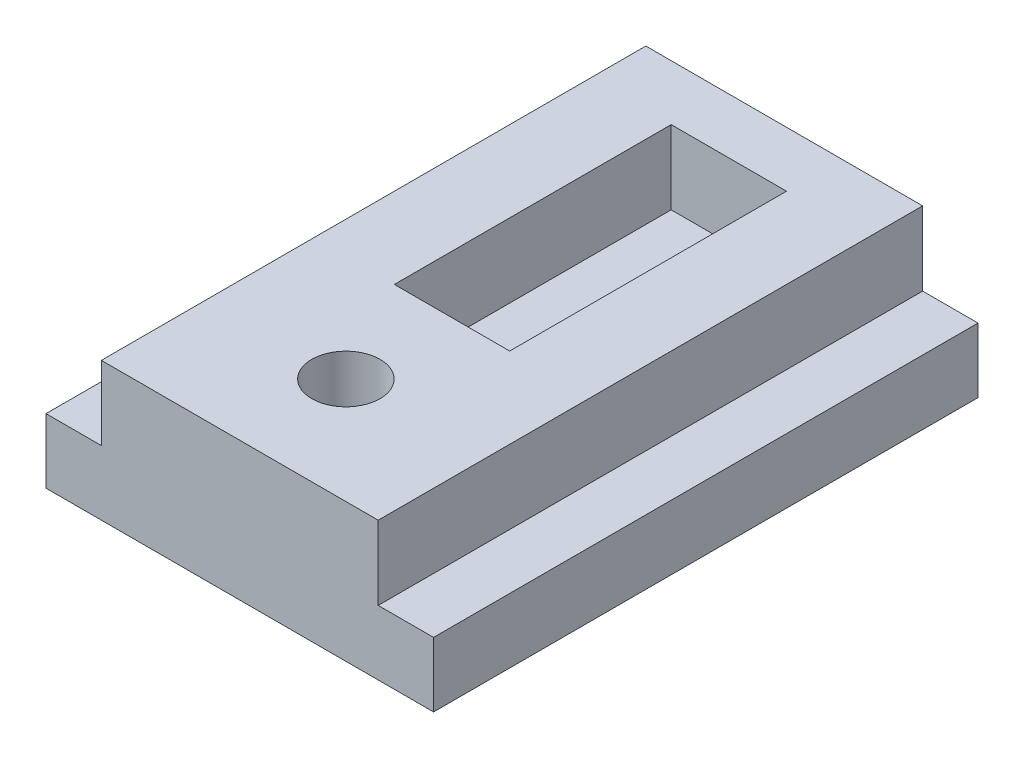
SolidWorks part; units mm, degrees
ref_plane "Front Plane" through (0, 0, 0) normal (0, 0, 1) x (1, 0, 0)
ref_plane "Top Plane" through (0, 0, 0) normal (0, 1, 0) x (1, 0, 0)
ref_plane "Right Plane" through (0, 0, 0) normal (1, 0, 0) x (0, 0, -1)
sketch "Sketch1" plane through (0, 0, 0) normal (0, 0, 1) x (1, 0, 0)
  line L0 (0, 3.75) -> (0, -3.75) construction
  line L2 (-7.5, -0.25) -> (-7.5, 3.75)
  line L3 (-7.5, 3.75) -> (7.5, 3.75)
  line L4 (7.5, -0.25) -> (7.5, 3.75)
  line L8 (-7.5, -0.25) -> (-10.5, -0.25)
  line L9 (-10.5, -3.75) -> (-10.5, -0.25)
  line L10 (-10.5, -3.75) -> (10.5, -3.75)
  line L12 (7.5, -0.25) -> (10.5, -0.25)
  line L13 (10.5, -3.75) -> (10.5, -0.25)
  dimension "D1" = 7.5
  dimension "D2" = 15
  dimension "D3" = 3.5
  dimension "D4" = 3
extrude "Boss-Extrude1" add sketch "Sketch1" along normal mid plane 29.5
ref_plane "Plane1" through (0, 0, -11.75) normal (0, 0, -1) x (-1, 0, 0)
sketch "Sketch3" plane through (0, 0, -11.75) normal (0, 0, -1) x (-1, 0, 0)
  line L1 (-3.125, -0.25) -> (3.125, -0.25)
  line L2 (-3.125, -0.25) -> (-3.125, 3.75)
  line L3 (-3.125, 3.75) -> (3.125, 3.75)
  line L4 (3.125, -0.25) -> (3.125, 3.75)
  line L5 (-7.5, 3.75) -> (7.5, 3.75) construction
  line L6 (0, 3.75) -> (0, 0) construction
  dimension "D1" = 6.25
  dimension "D2" = 4
extrude "Cut-Extrude1" cut sketch "Sketch3" against normal blind 15
hole_wizard "Ø3.7 (3.7) Diameter Hole1" positions "Sketch4" profile "Sketch5" hole size "Ø3.7" standard "ANSI Metric" end condition up to next
sketch "Sketch4" plane through (0, 3.75, 0) normal (0, 1, 0) x (1, 0, 0)
  line L0 (0, -3.25) -> (0, -14.75) construction
  line L1 (-3.125, -3.25) -> (3.125, -3.25) construction
  line L2 (7.5, -14.75) -> (-7.5, -14.75) construction
  point P0 (0, -9)
sketch "Sketch5" plane through (0, 3.75, 9) normal (1, 0, 0) x (0, 0, 1)
  line L0 (0, 0) -> (0, 7.5)
  line L1 (0, 7.5) -> (1.85, 7.5)
  line L2 (1.85, 7.5) -> (1.85, 0)
  line L5 (1.85, 0) -> (0, 0)
  line L11 (0, -6.35) -> (0, 107.95) construction
  dimension "Thru Hole Dia." = 3.7
  dimension "Thru Hole Depth" = 7.5
